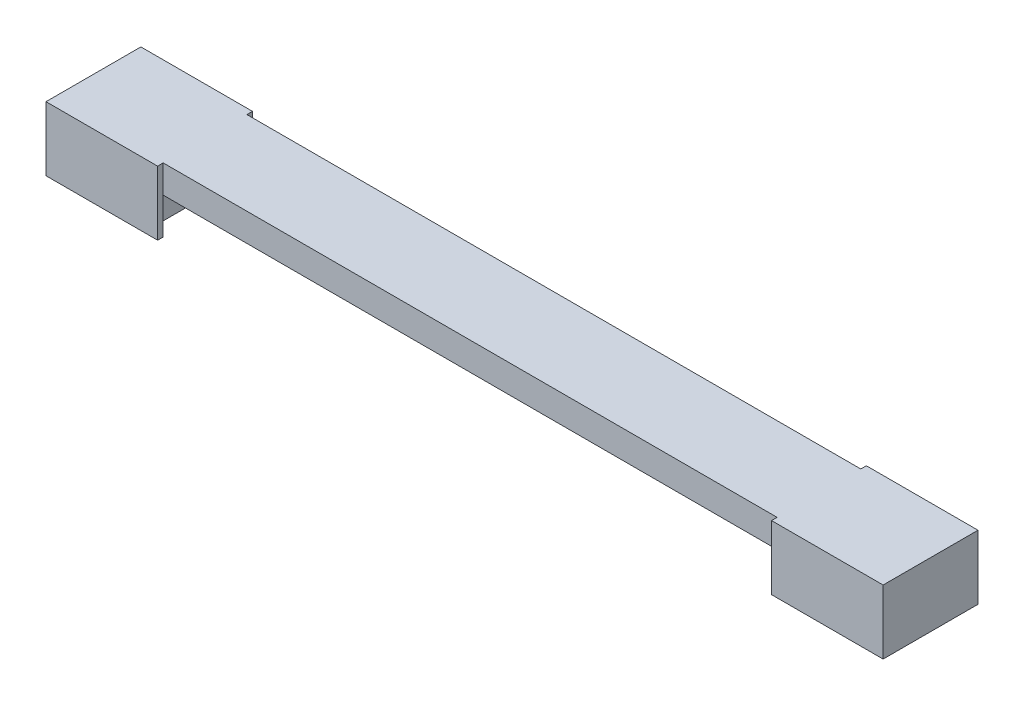
SolidWorks part; units mm, degrees
ref_plane "Ebene vorne" through (0, 0, 0) normal (0, 0, 1) x (1, 0, 0)
ref_plane "Ebene oben" through (0, 0, 0) normal (0, 1, 0) x (1, 0, 0)
ref_plane "Ebene rechts" through (0, 0, 0) normal (1, 0, 0) x (0, 0, -1)
sketch "Skizze1" plane through (0, 0, 0) normal (0, 0, 1) x (1, 0, 0)
  line L0 (0, 0) -> (31694.6402, 0) construction
  line L1 (0, 0) -> (0, 31694.6402) construction
  line L2 (-74, 0) -> (-74, -10)
  line L3 (-74, 0) -> (74, 0)
  line L5 (-56, -5) -> (56, -5)
  line L6 (-56, -10) -> (-74, -10)
  line L7 (-56, -5) -> (-56, -10)
  line L8 (56, -5) -> (56, -10)
  line L9 (56, -10) -> (74, -10)
  line L10 (74, 0) -> (74, -10)
  dimension "D1" = 56
  dimension "D2" = 5
  dimension "D3" = 5
  dimension "D4" = 18
extrude "Aufsatz-Linear austragen1" add sketch "Skizze1" along normal blind 15
sketch "Skizze5" plane through (0, -10, 0) normal (0, -1, 0) x (1, 0, 0)
  line L4 (56, 15) -> (56, 0) construction
  line L7 (56, 0) -> (55, 0)
  line L8 (55, -1) -> (75, -1)
  line L9 (75, -1) -> (75, 16)
  line L10 (75, 16) -> (55, 16)
  line L11 (55, 16) -> (55, -1)
  line L12 (56, -1) -> (75, -1)
  line L13 (75, -1) -> (75, 16)
  line L14 (75, 16) -> (56, 16)
  line L16 (56, 0) -> (74, 0)
  line L17 (74, 0) -> (74, 15)
  line L18 (74, 15) -> (56, 15)
  line L19 (56, 15) -> (56, 0)
  line L20 (56, 0) -> (74, 0)
  line L21 (74, 0) -> (74, 15)
  line L22 (74, 15) -> (56, 15)
  line L23 (56, -1) -> (55, -1)
  line L24 (55, 0) -> (55, -1)
  line L25 (56, 15) -> (55, 15)
  line L27 (56, 16) -> (55, 16)
  line L28 (55, 15) -> (55, 16)
  dimension "D3" = 1
  dimension "D1" = 1
  dimension "D2" = 0
extrude "Aufsatz-Linear austragen4" add sketch "Skizze5" along normal blind 1.5 and the other way up to surface other way up to face at (0, 0, 7.5)
mirror "Spiegeln1" about plane through (0, 0, 0) normal (1, 0, 0) of "Aufsatz-Linear austragen4"
